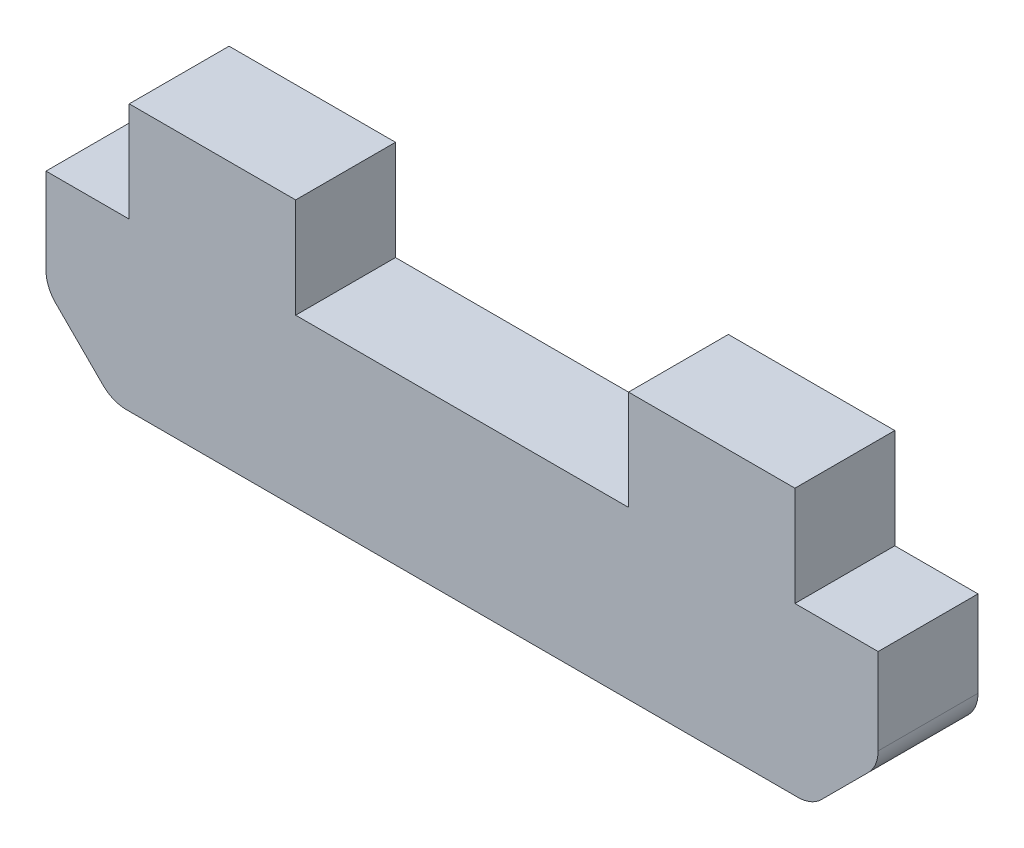
SolidWorks part; units mm, degrees
ref_plane "Front Plane" through (0, 0, 0) normal (0, 0, 1) x (1, 0, 0)
ref_plane "Top Plane" through (0, 0, 0) normal (0, 1, 0) x (1, 0, 0)
ref_plane "Right Plane" through (0, 0, 0) normal (1, 0, 0) x (0, 0, -1)
sketch "Sketch1" plane through (0, 0, 0) normal (0, 0, 1) x (1, 0, 0)
  line L0 (0, 0) -> (25, 0)
  line L1 (25, 0) -> (25, 5)
  line L2 (25, 5) -> (22.5, 5)
  line L3 (22.5, 5) -> (22.5, 8)
  line L4 (22.5, 8) -> (17.5, 8)
  line L5 (17.5, 8) -> (17.5, 5)
  line L6 (17.5, 5) -> (7.5, 5)
  line L7 (7.5, 5) -> (7.5, 8)
  line L8 (7.5, 8) -> (2.5, 8)
  line L9 (2.5, 8) -> (2.5, 5)
  line L10 (2.5, 5) -> (0, 5)
  line L11 (0, 5) -> (0, 0)
  dimension "D1" = 5
  dimension "D2" = 3
  dimension "D3" = 25
  dimension "D4" = 5
  dimension "D5" = 10
extrude "Boss-Extrude1" add sketch "Sketch1" along normal blind 3
chamfer "Chamfer1" distance 2 angle 45 2 edges at (25, 0, 1.5) (0, 0, 1.5)
fillet "Fillet1" radius 1 4 edges at (25, 2, 1.5) (23, 0, 1.5) (0, 2, 1.5) (2, 0, 1.5)
